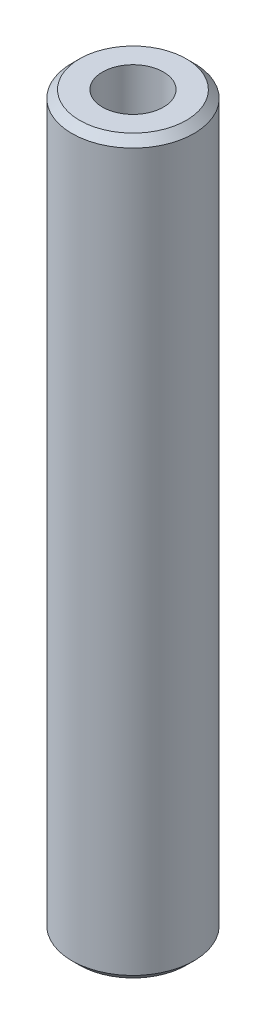
SolidWorks part; units mm, degrees
ref_plane "Front Plane" through (0, 0, 0) normal (0, 0, 1) x (1, 0, 0)
ref_plane "Top Plane" through (0, 0, 0) normal (0, 1, 0) x (1, 0, 0)
ref_plane "Right Plane" through (0, 0, 0) normal (1, 0, 0) x (0, 0, -1)
sketch "Sketch1" plane through (0, 0, 0) normal (0, 1, 0) x (1, 0, 0)
  circle A0 centre (0, 0) radius 2
  circle A1 centre (0, 0) radius 4
  dimension "D1" = 4
  dimension "D2" = 2
extrude "Boss-Extrude1" add sketch "Sketch1" along normal blind 48
chamfer "Chamfer1" distance 0.5 angle 45 2 edges at (0, 0, 4) (0, 48, 4)
